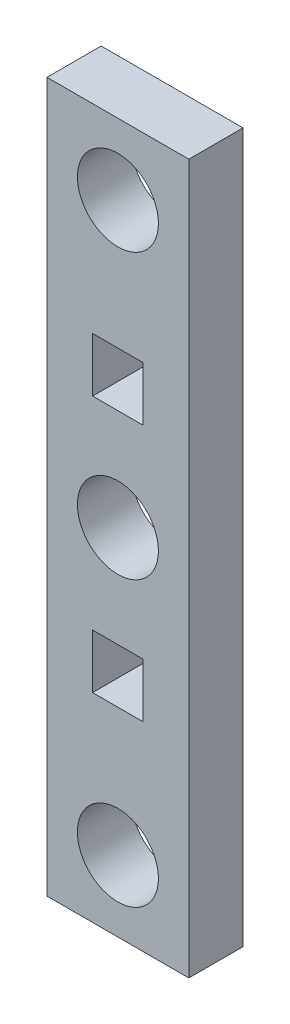
SolidWorks part; units mm, degrees
ref_plane "Front Plane" through (0, 0, 0) normal (0, 0, 1) x (1, 0, 0)
ref_plane "Top Plane" through (0, 0, 0) normal (0, 1, 0) x (1, 0, 0)
ref_plane "Right Plane" through (0, 0, 0) normal (1, 0, 0) x (0, 0, -1)
sketch "Model" plane through (0, 0, 0) normal (0, 0, 1) x (1, 0, 0)
  line L296 (9.5, 25) -> (4.5, 25)
  line L297 (4.5, 25) -> (4.5, 19.65)
  line L298 (4.5, 19.65) -> (9.5, 19.65)
  line L299 (9.5, 19.65) -> (9.5, 25)
  line L300 (0, 0) -> (14, 0)
  line L301 (0, 70) -> (0, 0)
  line L302 (14, 70) -> (0, 70)
  line L303 (14, 0) -> (14, 70)
  line L304 (4.5, 45) -> (9.5, 45)
  line L305 (9.5, 45) -> (9.5, 50.35)
  line L306 (9.5, 50.35) -> (4.5, 50.35)
  line L307 (4.5, 50.35) -> (4.5, 45)
  circle A40 centre (7, 63) radius 4
  circle A41 centre (7, 35) radius 4
  circle A42 centre (7, 7) radius 4
extrude "Boss-Extrude1" add sketch "Model" along normal blind 5.35
